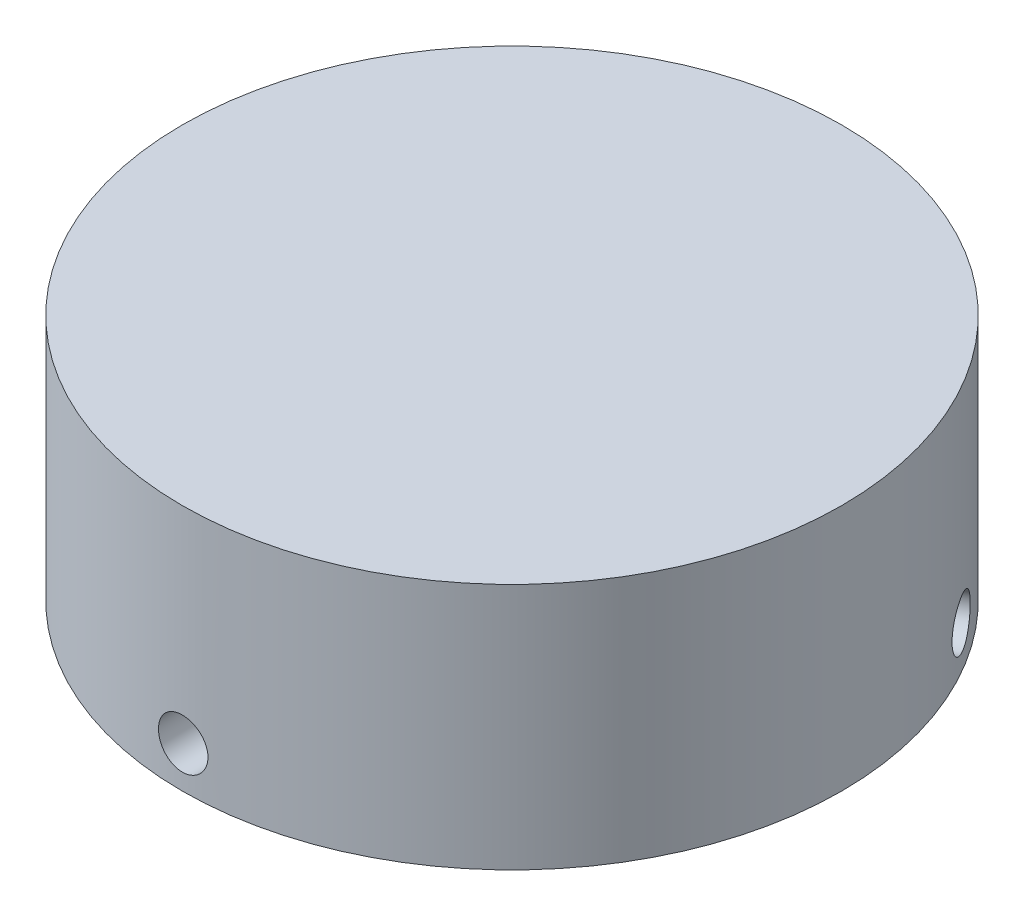
SolidWorks part; units mm, degrees
ref_plane "Front Plane" through (0, 0, 0) normal (0, 0, 1) x (1, 0, 0)
ref_plane "Top Plane" through (0, 0, 0) normal (0, 1, 0) x (1, 0, 0)
ref_plane "Right Plane" through (0, 0, 0) normal (1, 0, 0) x (0, 0, -1)
sketch "Sketch1" plane through (0, 0, 0) normal (0, 0, 1) x (1, 0, 0)
  line L1 (0, -63.9535) -> (0, 73.7209) construction
  line L2 (-40, 30) -> (0, 30)
  line L3 (0, 30) -> (0, 25)
  line L4 (0, 25) -> (-35, 25)
  line L7 (-35, 25) -> (-35, 0)
  line L8 (-35, 0) -> (-40, 0)
  line L9 (-40, 0) -> (-40, 30)
  point P9 (0, 0)
  point P10 (-40, 30)
  point P11 (0, 0)
  point P12 (-35, 0)
  point P15 (-35, -13.7551)
  point P16 (-35, 0)
  point P17 (0, 0)
  point P18 (0, 0)
  point P19 (-52.4679, 0)
  point P20 (-40, 13.8331)
  point P21 (-35, 19.0342)
  point P22 (0, 0)
  point P23 (-40, 22.9289)
  point P24 (0, 0)
  point P25 (0, 0)
  point P26 (-67.6189, 0)
  dimension "D1" = 5
  dimension "D2" = 30
  dimension "D6" = 40
  dimension "D7" = 5
revolve "Revolve1" add sketch "Sketch1" angle 360 about L1
ref_plane "Plane1" through (0, 0, 40) normal (0, 0, 1) x (1, 0, 0)
sketch "Sketch2" plane through (0, 0, 40) normal (0, 0, 1) x (1, 0, 0)
  line L0 (0, -27.9441) -> (0, 37.3854) construction
  line L1 (-40, 0) -> (40, 0) construction
  line L2 (-40, 0) -> (40, 0) construction
  circle A0 centre (0, 5) radius 3
  dimension "D2" = 6
  dimension "D1" = 5
extrude "Cut-Extrude1" cut sketch "Sketch2" against normal up to next
pattern_circular "CirPattern1" count 3 over 360 about axis through (0, -63.9535, 0) along (0, 1, 0) of "Cut-Extrude1"
